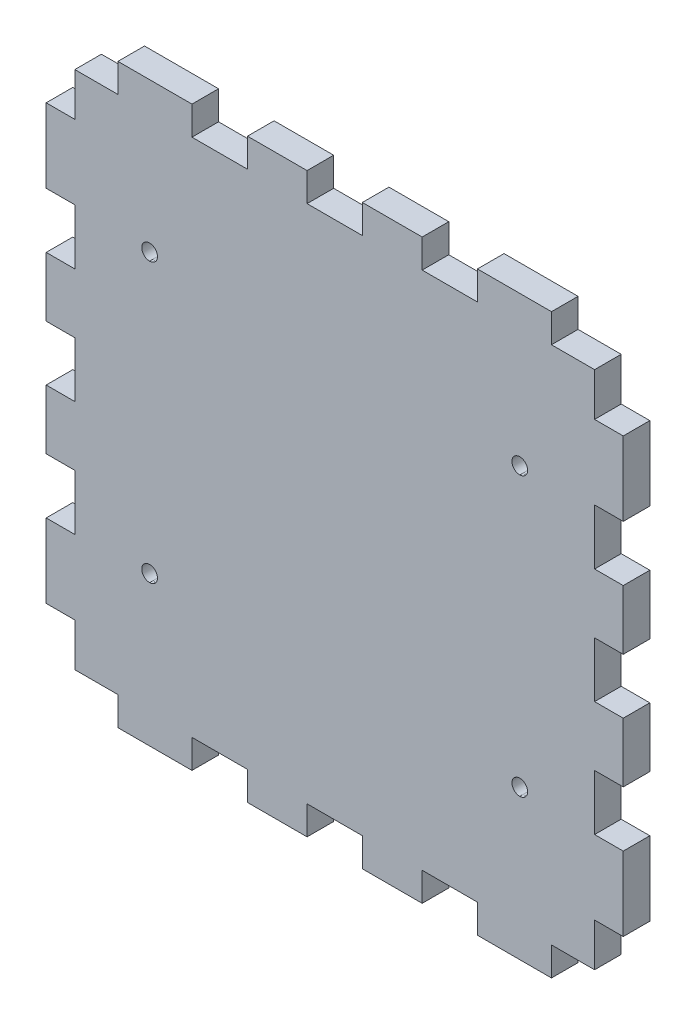
SolidWorks part; units mm, degrees
ref_plane "Front Plane" through (0, 0, 0) normal (0, 0, 1) x (1, 0, 0)
ref_plane "Top Plane" through (0, 0, 0) normal (0, 1, 0) x (1, 0, 0)
ref_plane "Right Plane" through (0, 0, 0) normal (1, 0, 0) x (0, 0, -1)
sketch "Model" plane through (0, 0, 0) normal (0, 0, 1) x (1, 0, 0)
  line L0 (-5.9972, 216.8283) -> (0, 216.8283)
  line L1 (0, 216.8283) -> (0, 220.8147)
  line L2 (0, 220.8147) -> (10.3011, 220.8147)
  line L3 (10.3011, 220.8147) -> (10.3011, 216.8283)
  line L4 (10.3011, 216.8283) -> (18.0269, 216.8283)
  line L5 (18.0269, 216.8283) -> (18.0269, 220.8147)
  line L6 (18.0269, 220.8147) -> (26.3172, 220.8147)
  line L7 (26.3172, 220.8147) -> (26.3172, 216.8283)
  line L8 (26.3172, 216.8283) -> (34.0078, 216.8283)
  line L9 (34.0078, 216.8283) -> (34.0078, 220.8147)
  line L10 (34.0078, 220.8147) -> (42.3333, 220.8147)
  line L11 (42.3333, 220.8147) -> (42.3333, 216.8283)
  line L12 (42.3333, 216.8283) -> (50.0239, 216.8283)
  line L13 (50.0239, 216.8283) -> (50.0239, 220.8147)
  line L14 (50.0239, 220.8147) -> (60.325, 220.8147)
  line L15 (60.325, 220.8147) -> (60.325, 216.8283)
  line L16 (60.325, 216.8283) -> (66.3222, 216.8283)
  line L17 (66.3222, 216.8283) -> (66.3222, 210.8311)
  line L18 (66.3222, 210.8311) -> (70.3086, 210.8311)
  line L19 (70.3086, 210.8311) -> (70.3086, 200.53)
  line L20 (70.3086, 200.53) -> (66.3222, 200.53)
  line L21 (66.3222, 200.53) -> (66.3222, 192.8042)
  line L22 (66.3222, 192.8042) -> (70.3086, 192.8042)
  line L23 (70.3086, 192.8042) -> (70.3086, 184.5139)
  line L24 (70.3086, 184.5139) -> (66.3222, 184.5139)
  line L25 (66.3222, 184.5139) -> (66.3222, 176.8233)
  line L26 (66.3222, 176.8233) -> (70.3086, 176.8233)
  line L27 (70.3086, 176.8233) -> (70.3086, 168.533)
  line L28 (70.3086, 168.533) -> (66.3222, 168.533)
  line L29 (66.3222, 168.533) -> (66.3222, 160.8072)
  line L30 (66.3222, 160.8072) -> (70.3086, 160.8072)
  line L31 (70.3086, 160.8072) -> (70.3086, 150.5061)
  line L32 (70.3086, 150.5061) -> (66.3222, 150.5061)
  line L33 (66.3222, 150.5061) -> (66.3222, 144.5089)
  line L34 (66.3222, 144.5089) -> (60.325, 144.5089)
  line L35 (60.325, 144.5089) -> (60.325, 140.5225)
  line L36 (60.325, 140.5225) -> (50.0239, 140.5225)
  line L37 (50.0239, 140.5225) -> (50.0239, 144.5089)
  line L38 (50.0239, 144.5089) -> (42.3333, 144.5089)
  line L39 (42.3333, 144.5089) -> (42.3333, 140.5225)
  line L40 (42.3333, 140.5225) -> (34.0078, 140.5225)
  line L41 (34.0078, 140.5225) -> (34.0078, 144.5089)
  line L42 (34.0078, 144.5089) -> (26.3172, 144.5089)
  line L43 (26.3172, 144.5089) -> (26.3172, 140.5225)
  line L44 (26.3172, 140.5225) -> (18.0269, 140.5225)
  line L45 (18.0269, 140.5225) -> (18.0269, 144.5089)
  line L46 (18.0269, 144.5089) -> (10.3011, 144.5089)
  line L47 (10.3011, 144.5089) -> (10.3011, 140.5225)
  line L48 (10.3011, 140.5225) -> (0, 140.5225)
  line L49 (0, 140.5225) -> (0, 144.5089)
  line L50 (0, 144.5089) -> (-5.9972, 144.5089)
  line L51 (-5.9972, 144.5089) -> (-5.9972, 150.5061)
  line L52 (-5.9972, 150.5061) -> (-9.9836, 150.5061)
  line L53 (-9.9836, 150.5061) -> (-9.9836, 160.8072)
  line L54 (-9.9836, 160.8072) -> (-5.9972, 160.8072)
  line L55 (-5.9972, 160.8072) -> (-5.9972, 168.533)
  line L56 (-5.9972, 168.533) -> (-9.9836, 168.533)
  line L57 (-9.9836, 168.533) -> (-9.9836, 176.8233)
  line L58 (-9.9836, 176.8233) -> (-5.9972, 176.8233)
  line L59 (-5.9972, 176.8233) -> (-5.9972, 184.5139)
  line L60 (-5.9972, 184.5139) -> (-9.9836, 184.5139)
  line L61 (-9.9836, 184.5139) -> (-9.9836, 192.8042)
  line L62 (-9.9836, 192.8042) -> (-5.9972, 192.8042)
  line L63 (-5.9972, 192.8042) -> (-5.9972, 200.53)
  line L64 (-5.9972, 200.53) -> (-9.9836, 200.53)
  line L65 (-9.9836, 200.53) -> (-9.9836, 210.8311)
  line L66 (-9.9836, 210.8311) -> (-5.9972, 210.8311)
  line L67 (-5.9972, 210.8311) -> (-5.9972, 216.8283)
  spline S0 degree 3 poles (4.4097, 198.9404) (3.8057, 198.9404) (3.3161, 199.43) (3.3161, 200.034) (3.3161, 200.638) (3.8057, 201.1276) (4.4097, 201.1276) knots 2 2 2 2 3 3 3 4 4 4 4
  spline S1 degree 3 poles (4.4097, 201.1276) (5.0137, 201.1276) (5.5033, 200.638) (5.5033, 200.034) (5.5033, 199.43) (5.0137, 198.9404) (4.4097, 198.9404) knots 0 0 0 0 1 1 1 2 2 2 2
  spline S2 degree 3 poles (55.9153, 160.2054) (55.3113, 160.2054) (54.8217, 160.695) (54.8217, 161.299) (54.8217, 161.903) (55.3113, 162.3926) (55.9153, 162.3926) knots 2 2 2 2 3 3 3 4 4 4 4
  spline S3 degree 3 poles (55.9153, 162.3926) (56.5193, 162.3926) (57.0089, 161.903) (57.0089, 161.299) (57.0089, 160.695) (56.5193, 160.2054) (55.9153, 160.2054) knots 0 0 0 0 1 1 1 2 2 2 2
  spline S4 degree 3 poles (4.4097, 160.2054) (3.8057, 160.2054) (3.3161, 160.695) (3.3161, 161.299) (3.3161, 161.903) (3.8057, 162.3926) (4.4097, 162.3926) knots 2 2 2 2 3 3 3 4 4 4 4
  spline S5 degree 3 poles (4.4097, 162.3926) (5.0137, 162.3926) (5.5033, 161.903) (5.5033, 161.299) (5.5033, 160.695) (5.0137, 160.2054) (4.4097, 160.2054) knots 0 0 0 0 1 1 1 2 2 2 2
  spline S6 degree 3 poles (55.9153, 198.9404) (55.3113, 198.9404) (54.8217, 199.43) (54.8217, 200.034) (54.8217, 200.638) (55.3113, 201.1276) (55.9153, 201.1276) knots 2 2 2 2 3 3 3 4 4 4 4
  spline S7 degree 3 poles (55.9153, 201.1276) (56.5193, 201.1276) (57.0089, 200.638) (57.0089, 200.034) (57.0089, 199.43) (56.5193, 198.9404) (55.9153, 198.9404) knots 0 0 0 0 1 1 1 2 2 2 2
extrude "Boss-Extrude1" add sketch "Model" along normal blind 3.7
